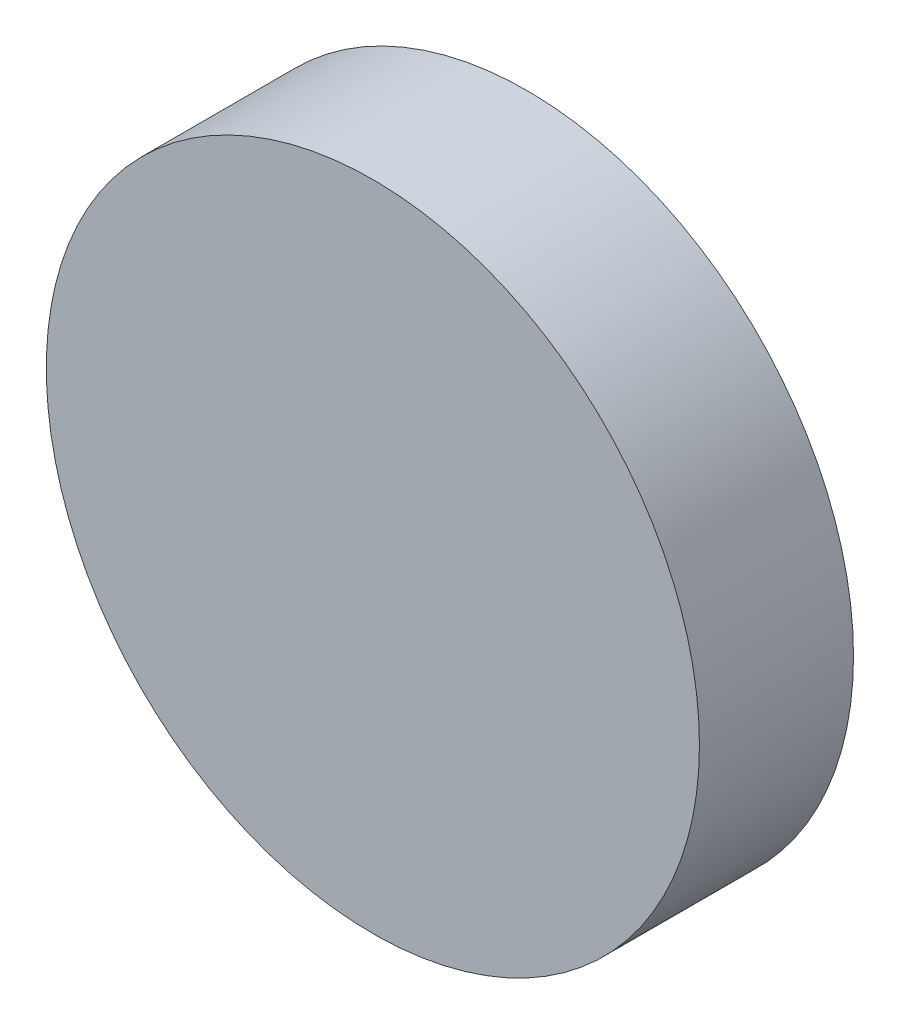
SolidWorks part; units mm, degrees
ref_plane "Front Plane" through (0, 0, 0) normal (0, 0, 1) x (1, 0, 0)
ref_plane "Top Plane" through (0, 0, 0) normal (0, 1, 0) x (1, 0, 0)
ref_plane "Right Plane" through (0, 0, 0) normal (1, 0, 0) x (0, 0, -1)
sketch "Sketch1" plane through (0, 0, 0) normal (0, 0, 1) x (1, 0, 0)
  circle A0 centre (0, 0) radius 49.53
  dimension "D1" = 99.06
extrude "Boss-Extrude1" add sketch "Sketch1" along normal blind 23.368
